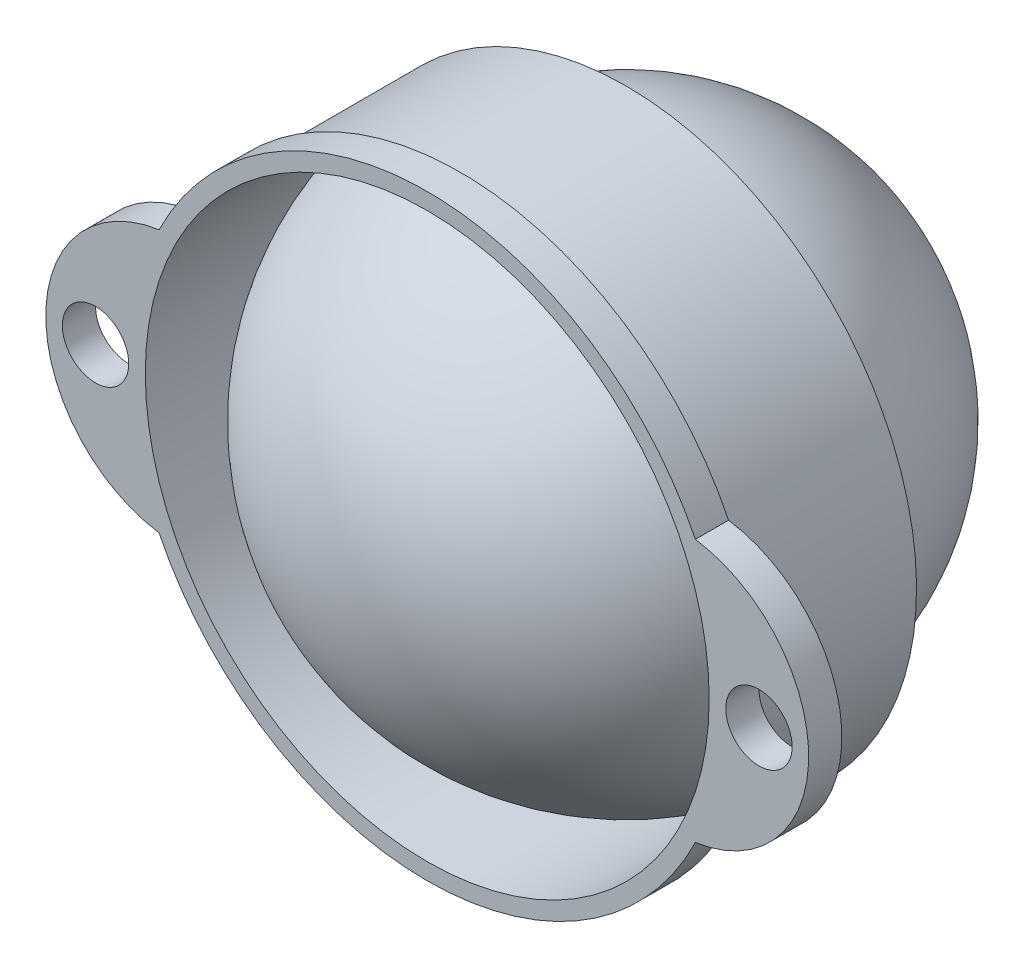
SolidWorks part; units mm, degrees
ref_plane "Front Plane" through (0, 0, 0) normal (0, 0, 1) x (1, 0, 0)
ref_plane "Top Plane" through (0, 0, 0) normal (0, 1, 0) x (1, 0, 0)
ref_plane "Right Plane" through (0, 0, 0) normal (1, 0, 0) x (0, 0, -1)
sketch "Sketch1" plane through (0, 0, 0) normal (0, 0, 1) x (1, 0, 0)
  line L0 (-15, 0) -> (15, 0)
  arc A0 (15, 0) -> (-15, 0) centre (0, 0) ccw
revolve "Revolve4" add sketch "Sketch1" angle 360 about L0
sketch "Sketch5" plane through (0, 0, 0) normal (0, 0, 1) x (1, 0, 0)
  line L0 (-17, 0) -> (-15, 0)
  line L1 (15, 0) -> (17, 0)
  arc A0 (15, 0) -> (-15, 0) centre (0, 0) ccw
  arc A1 (17, 0) -> (-17, 0) centre (0, 0) ccw
revolve "Revolve5" add sketch "Sketch5" angle 180 about L0
sketch "Sketch6" plane through (0, 0, 0) normal (0, 0, -1) x (-1, 0, 0)
  line L2 (22.9981, 0) -> (23, 0)
  line L3 (15, -7.9962) -> (15, -8)
  circle A1 centre (20, 0) radius 2
  arc A2 (15, -8) -> (15, 8) centre (0, 0) ccw
  arc A3 (15, -7.9962) -> (15, 8) centre (15, 0.0019) ccw
  circle A4 centre (-20, 0) radius 2
  arc A5 (-15, -8) -> (-15, 8) centre (0, 0) cw
  arc A6 (-15, -7.9962) -> (-15, 8) centre (-15, 0.0019) cw
  circle M7 centre (0, 0) radius 17
extrude "Boss-Extrude2" add sketch "Sketch6" against normal blind 19 separate body contours A2 A3 A1 | A6 A4 M7
sketch "Sketch7" plane through (0, 0, 19) normal (0, 0, 1) x (1, 0, 0)
  circle A0 centre (0, 0) radius 17
  circle A1 centre (0, 0) radius 18
extrude "Boss-Extrude3" add sketch "Sketch7" against normal blind 19
sketch "Sketch8" plane through (0, 0, 0) normal (0, 0, -1) x (-1, 0, 0)
  arc A0 (-16.1687, -7.9104) -> (16.1687, -7.9104) centre (0, 0) ccw
  arc A1 (-16.1667, 7.9145) -> (-16.1687, -7.9104) centre (-15, 0.0019) ccw
  arc A2 (16.1667, 7.9145) -> (16.1687, -7.9104) centre (15, 0.0019) cw
  arc A3 (16.1667, 7.9145) -> (-16.1667, 7.9145) centre (0, 0) ccw
  circle A4 centre (0, 0) radius 17.5
extrude "Cut-Extrude5" cut sketch "Sketch8" against normal blind 10
sketch "Sketch10" plane through (0, 0, 19) normal (0, 0, 1) x (1, 0, 0)
  circle A0 centre (0, 0) radius 17.5
  arc A1 (16.1667, 7.9145) -> (-16.1667, 7.9145) centre (0, 0) ccw
  arc A2 (-16.1667, 7.9145) -> (-16.1687, -7.9104) centre (-15, 0.0019) ccw
  arc A3 (16.1667, 7.9145) -> (16.1687, -7.9104) centre (15, 0.0019) cw
  arc A4 (-16.1687, -7.9104) -> (16.1687, -7.9104) centre (0, 0) ccw
extrude "Cut-Extrude6" cut sketch "Sketch10" against normal blind 7
sketch "Sketch11" plane through (0, 0, 19) normal (0, 0, 1) x (1, 0, 0)
  circle A0 centre (0, 0) radius 17.5
  circle A1 centre (0, 0) radius 17
extrude "Cut-Extrude7" cut sketch "Sketch11" against normal blind 7
